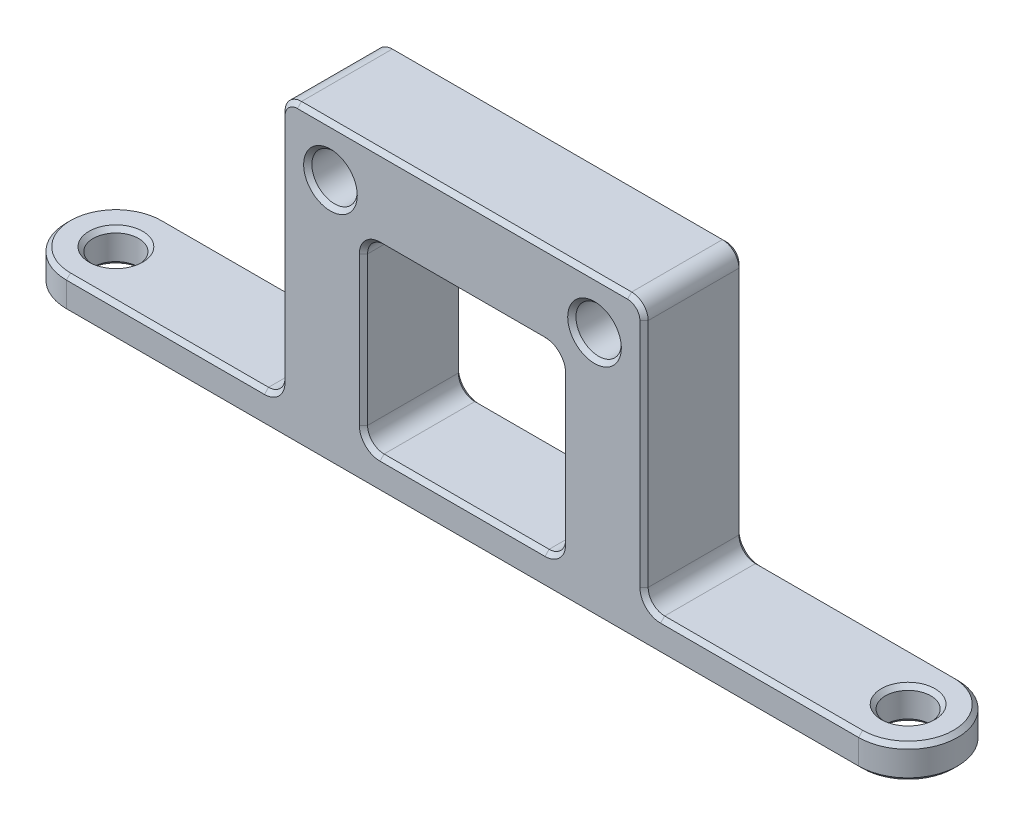
SolidWorks part; units mm, degrees
ref_plane "Front Plane" through (0, 0, 0) normal (0, 0, 1) x (1, 0, 0)
ref_plane "Top Plane" through (0, 0, 0) normal (0, 1, 0) x (1, 0, 0)
ref_plane "Right Plane" through (0, 0, 0) normal (1, 0, 0) x (0, 0, -1)
sketch "Sketch2" plane through (0, 0, 0) normal (0, 1, 0) x (1, 0, 0)
  line L0 (-38.1, 0) -> (38.1, 0) construction
  line L5 (-38.1, 4.7625) -> (38.1, 4.7625)
  line L6 (-38.1, -4.7625) -> (38.1, -4.7625)
  circle A0 centre (-38.1, 0) radius 2.1828
  circle A1 centre (38.1, 0) radius 2.1828
  arc A2 (-38.1, 4.7625) -> (-38.1, -4.7625) centre (-38.1, 0) ccw
  arc A3 (38.1, -4.7625) -> (38.1, 4.7625) centre (38.1, 0) ccw
  point P0 (0, 0)
  point P1 (0, 0)
  dimension "D3" = 4.3656
  dimension "D4" = 4.3656
  dimension "D5" = 4.7625
  dimension "D1" = 38.1
  dimension "D2" = 38.1
extrude "Boss-Extrude1" add sketch "Sketch2" along normal blind 3.175
sketch "Sketch3" plane through (0, 3.175, 0) normal (0, 1, 0) x (1, 0, 0)
  line L0 (38.1, 4.7625) -> (-38.1, 4.7625) construction
  line L1 (-18.4216, -4.7625) -> (18.4216, -4.7625)
  line L2 (-18.4216, -4.7625) -> (-18.4216, 4.7625)
  line L3 (-18.4216, 4.7625) -> (18.4216, 4.7625)
  line L4 (18.4216, -4.7625) -> (18.4216, 4.7625)
  line L5 (-18.4216, -4.7625) -> (18.4216, 4.7625) construction
  line L6 (-18.4216, 4.7625) -> (18.4216, -4.7625) construction
  point P0 (0, 0)
  dimension "D1" = 36.8432
extrude "Boss-Extrude2" add sketch "Sketch3" along normal blind 25.4
sketch "Sketch4" plane through (0, 0, 4.7625) normal (0, 0, 1) x (1, 0, 0)
  line L0 (-18.4216, 28.575) -> (18.4216, 28.575) construction
  line L1 (-38.1, 3.175) -> (-18.4216, 3.175) construction
  line L2 (-18.4216, 28.575) -> (-17.4625, 28.575)
  line L3 (-18.4216, 28.575) -> (-18.4216, 3.175)
  line L4 (-18.4216, 3.175) -> (-17.4625, 3.175)
  line L5 (-17.4625, 28.575) -> (-17.4625, 3.175)
  line L6 (18.4216, 3.175) -> (38.1, 3.175) construction
  line L7 (18.4216, 28.575) -> (17.4625, 28.575)
  line L8 (18.4216, 28.575) -> (18.4216, 3.175)
  line L9 (18.4216, 3.175) -> (17.4625, 3.175)
  line L10 (17.4625, 28.575) -> (17.4625, 3.175)
  line L12 (-9.525, 3.175) -> (9.525, 3.175)
  line L13 (-9.525, 3.175) -> (-9.525, 20.6375)
  line L14 (-9.525, 20.6375) -> (9.525, 20.6375)
  line L15 (9.525, 3.175) -> (9.525, 20.6375)
  circle A0 centre (-12.7, 23.8125) radius 2.1828
  circle A1 centre (12.7, 23.8125) radius 2.1828
  dimension "D6" = 4.3656
  dimension "D7" = 4.3656
  dimension "D1" = 12.7
  dimension "D2" = 12.7
  dimension "D3" = 4.7625
  dimension "D4" = 4.7625
  dimension "D5" = 4.7625
  dimension "D8" = 4.7625
  dimension "D9" = 3.175
  dimension "D10" = 3.175
  dimension "D11" = 3.175
extrude "Cut-Extrude1" cut sketch "Sketch4" against normal through all both and the other way through all
fillet "Fillet1" radius 1.5875 8 edges at (-17.4625, 28.575, 0) (-17.4625, 3.175, 0) (17.4625, 28.575, 0) (17.4625, 3.175, 0) (-9.525, 20.6375, 0) (9.525, 20.6375, 0) (9.525, 3.175, 0) (-9.525, 3.175, 0)
chamfer "Chamfer1" distance 0.3969 angle 45 48 edges at (-14.8828, 23.8125, 4.7625) (-10.5172, 23.8125, -4.7625) (10.5172, 23.8125, 4.7625) (14.8828, 23.8125, -4.7625) (38.1, 3.175, 2.1828) (-38.1, 3.175, 2.1828) (0, 20.6375, -4.7625) (-9.06, 20.1725, -4.7625) (9.06, 20.1725, -4.7625) (-9.525, 11.9062, -4.7625) (9.525, 11.9063, -4.7625) (-9.06, 3.64, -4.7625) (9.06, 3.64, -4.7625) (0, 3.175, -4.7625) (0, 20.6375, 4.7625) (9.06, 20.1725, 4.7625) (-9.06, 20.1725, 4.7625) (9.525, 11.9063, 4.7625) (-9.525, 11.9062, 4.7625) (9.06, 3.64, 4.7625) (-9.06, 3.64, 4.7625) (0, 3.175, 4.7625) (38.1, 0, 2.1828) (-38.1, 0, 2.1828) (0, 0, 4.7625) (42.8625, 0, 0) (0, 0, -4.7625) (-42.8625, 0, 0) (0, 28.575, 4.7625) (16.9975, 28.11, 4.7625) (-16.9975, 28.11, 4.7625) (17.4625, 15.875, 4.7625) (-17.4625, 15.875, 4.7625) (17.9275, 3.64, 4.7625) (-17.9275, 3.64, 4.7625) (28.575, 3.175, 4.7625) (-28.575, 3.175, 4.7625) (42.8625, 3.175, 0) (-42.8625, 3.175, 0) (28.575, 3.175, -4.7625) (-28.575, 3.175, -4.7625) (17.9275, 3.64, -4.7625) (-17.9275, 3.64, -4.7625) (17.4625, 15.875, -4.7625) (-17.4625, 15.875, -4.7625) (16.9975, 28.11, -4.7625) (-16.9975, 28.11, -4.7625) (0, 28.575, -4.7625)
